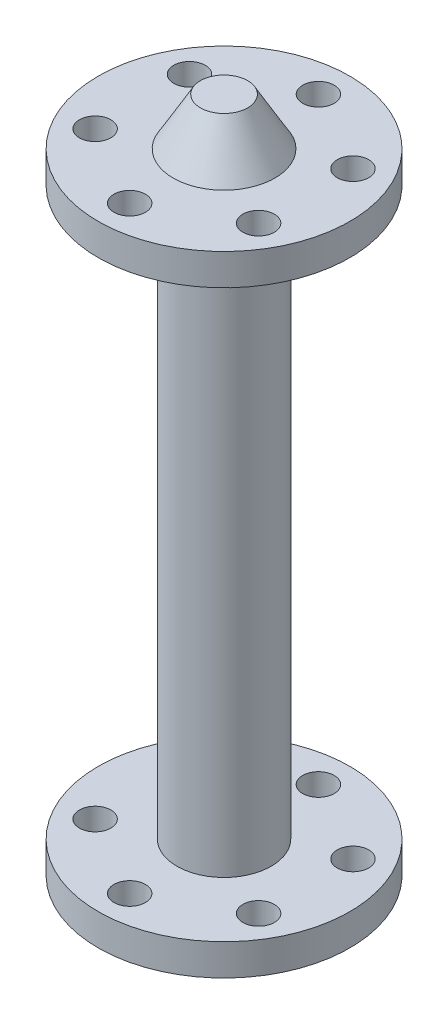
SolidWorks part; units mm, degrees
ref_plane "Front Plane" through (0, 0, 0) normal (0, 0, 1) x (1, 0, 0)
ref_plane "Top Plane" through (0, 0, 0) normal (0, 1, 0) x (1, 0, 0)
ref_plane "Right Plane" through (0, 0, 0) normal (1, 0, 0) x (0, 0, -1)
sketch "Sketch1" plane through (0, 0, 0) normal (0, 0, 1) x (1, 0, 0)
  line L0 (0, 72.473) -> (0, -62.352) construction
  line L1 (0, 72.473) -> (15, 72.473)
  line L2 (15, 72.473) -> (32.3205, 42.473)
  line L3 (32.3205, 42.473) -> (80, 42.473)
  line L4 (80, 42.473) -> (80, 22.473)
  line L5 (80, 22.473) -> (30, 22.473)
  line L6 (30, 22.473) -> (30, -337.527)
  line L7 (30, -337.527) -> (80, -337.527)
  line L8 (80, -337.527) -> (80, -357.527)
  line L9 (80, -357.527) -> (32.3205, -357.527)
  line L10 (32.3205, -357.527) -> (15, -387.527)
  line L11 (15, -387.527) -> (0, -387.527)
  line L12 (0, -387.527) -> (0, -62.352) construction
  line L13 (0, 72.473) -> (0, -387.527)
  dimension "D1" = 15
  dimension "D2" = 30
  dimension "D3" = 20
  dimension "D4" = 30
  dimension "D5" = 460
  dimension "D6" = 360
  dimension "D7" = 20
  dimension "D8" = 30
  dimension "D9" = 80
  dimension "D10" = 30
revolve "Revolve1" add sketch "Sketch1" angle 360 about L13
hole_wizard "Ø1.0mm Dowel Hole1" positions "Sketch6" profile "Sketch8" hole size "Ø1.0" standard "ISO" end condition through all
sketch "Sketch6" plane through (0, 42.473, 0) normal (0, 1, 0) x (1, 0, 0)
  point P0 (0, 60)
  dimension "D1" = 60
sketch "Sketch8" plane through (0, 42.473, -60) normal (1, 0, 0) x (0, 0, 1)
  line L0 (0, 0) -> (0, 430)
  line L1 (0, 430) -> (10, 430)
  line L2 (10, 430) -> (10, 0)
  line L5 (10, 0) -> (0, 0)
  line L11 (0, -6.35) -> (0, 107.95) construction
  dimension "Thru Hole Dia." = 20
  dimension "Thru Hole Depth" = 430
pattern_circular "CirPattern1" count 6 over 360 about axis through (0, 0, 0) along (0, 1, 0) of "Ø1.0mm Dowel Hole1"
